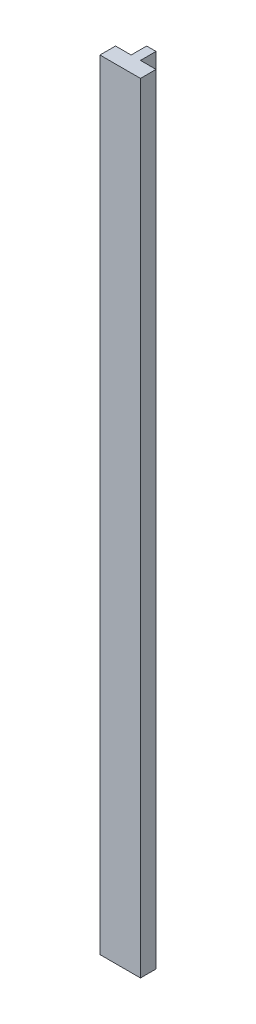
SolidWorks part; units mm, degrees
ref_plane "前视基准面" through (0, 0, 0) normal (0, 0, 1) x (1, 0, 0)
ref_plane "上视基准面" through (0, 0, 0) normal (0, 1, 0) x (1, 0, 0)
ref_plane "右视基准面" through (0, 0, 0) normal (1, 0, 0) x (0, 0, -1)
sketch "草图2" plane through (0, 0, 0) normal (0, 1, 0) x (1, 0, 0)
  line L0 (0, 0) -> (10, 0)
  line L1 (10, 0) -> (10, 10)
  line L2 (10, 10) -> (16, 10)
  line L3 (16, 10) -> (16, 0)
  line L4 (16, 0) -> (26, 0)
  line L5 (26, 0) -> (26, -10)
  line L6 (26, -10) -> (0, -10)
  line L7 (0, -10) -> (0, 0)
  dimension "D1" = 10
  dimension "D2" = 6
  dimension "D3" = 10
  dimension "D4" = 10
  dimension "D5" = 10
extrude "凸台-拉伸1" add sketch "草图2" along normal blind 500
